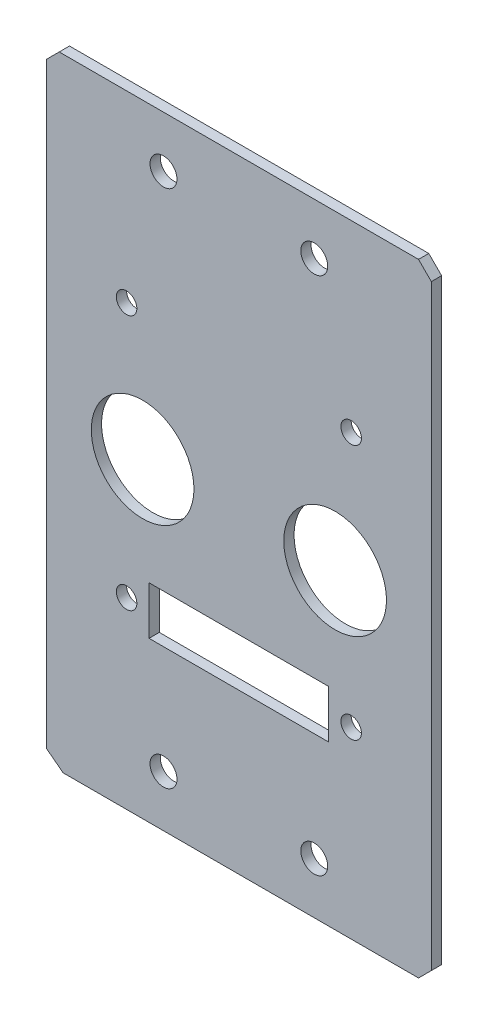
SolidWorks part; units mm, degrees
ref_plane "前视基准面" through (0, 0, 0) normal (0, 0, 1) x (1, 0, 0)
ref_plane "上视基准面" through (0, 0, 0) normal (0, 1, 0) x (1, 0, 0)
ref_plane "右视基准面" through (0, 0, 0) normal (1, 0, 0) x (0, 0, -1)
sketch "草图1" plane through (0, 0, 0) normal (0, 0, 1) x (1, 0, 0)
  line L0 (-92.1038, 0) -> (123.6031, 0) construction
  line L1 (-28, 48.5) -> (28, 48.5)
  line L2 (-30, 46.5) -> (-30, -46.5)
  line L3 (-27.3896, -48.5) -> (28, -48.5)
  line L4 (30, 46.5) -> (30, -46.5)
  line L5 (0, 53.0447) -> (0, -100.1676) construction
  line L6 (-35.7434, -19.9) -> (41.482, -19.9) construction
  line L7 (-30, 46.5) -> (-28, 48.5)
  line L8 (-14, -16.15) -> (14, -16.15)
  line L9 (-14, -16.15) -> (-14, -23.65)
  line L10 (-14, -23.65) -> (14, -23.65)
  line L11 (14, -16.15) -> (14, -23.65)
  line L12 (28, 48.5) -> (30, 46.5)
  line L13 (28, -48.5) -> (30, -46.5)
  line L14 (-30, -46.5) -> (-27.3896, -48.5)
  circle A0 centre (-15, 0) radius 8
  circle A1 centre (-17.5, 19.9) radius 1.6
  circle A2 centre (-11.75, 40.5) radius 2.1
  circle A3 centre (-17.5, -19.9) radius 1.6
  circle A4 centre (-11.75, -40.5) radius 2.1
  circle A5 centre (17.5, 19.9) radius 1.6
  circle A6 centre (11.75, 40.5) radius 2.1
  circle A7 centre (11.75, -40.5) radius 2.1
  circle A8 centre (17.5, -19.9) radius 1.6
  circle A9 centre (15, 0) radius 8
  dimension "D4" = 16
  dimension "D5" = 3.2
  dimension "D6" = 4.2
  dimension "D2" = 11.75
  dimension "D3" = 30
  dimension "D7" = 28.6
  dimension "D8" = 8
  dimension "D9" = 28
  dimension "D10" = 7.5
extrude "凸台-拉伸1" add sketch "草图1" along normal blind 1.6
